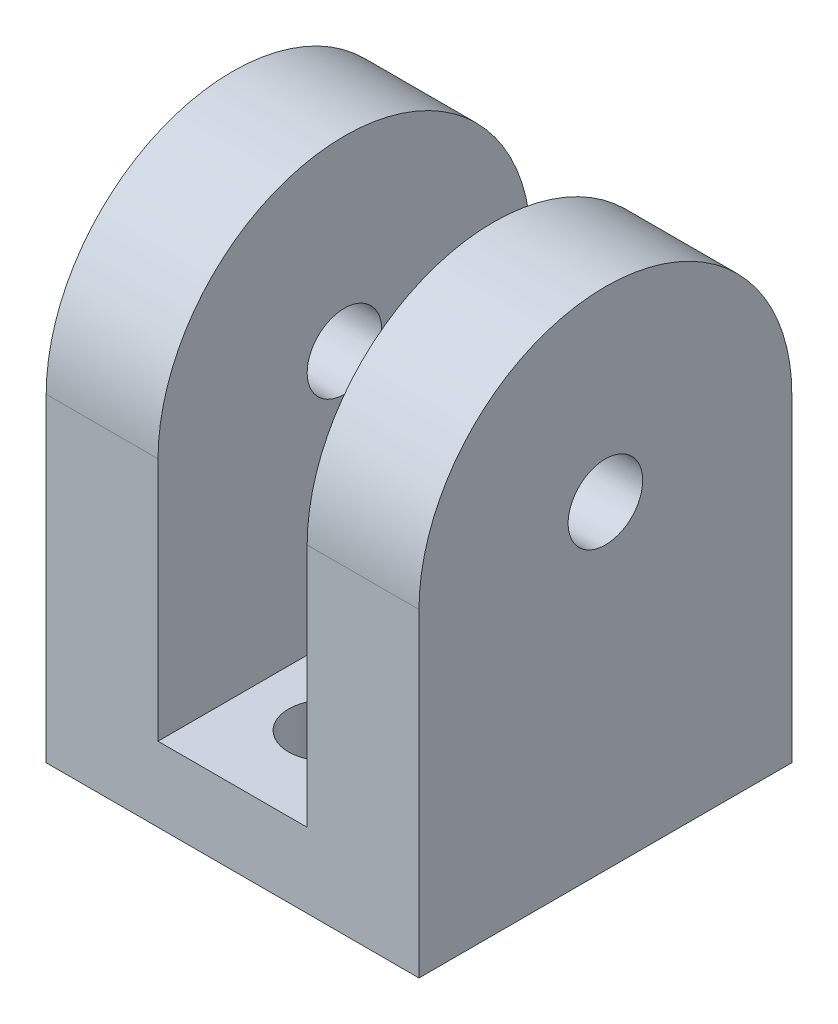
SolidWorks part; units mm, degrees
ref_plane "Front Plane" through (0, 0, 0) normal (0, 0, 1) x (1, 0, 0)
ref_plane "Top Plane" through (0, 0, 0) normal (0, 1, 0) x (1, 0, 0)
ref_plane "Right Plane" through (0, 0, 0) normal (1, 0, 0) x (0, 0, -1)
sketch "Sketch1" plane through (0, 0, 0) normal (0, 1, 0) x (1, 0, 0)
  line L1 (0, 0) -> (31.75, 0)
  line L2 (0, 0) -> (0, 31.75)
  line L3 (0, 31.75) -> (31.75, 31.75)
  line L4 (31.75, 0) -> (31.75, 31.75)
  dimension "D1" = 31.75
  dimension "D2" = 31.75
extrude "Boss-Extrude1" add sketch "Sketch1" along normal blind 50.8
sketch "Sketch2" plane through (31.75, 0, 0) normal (1, 0, 0) x (0, 0, -1)
  line L0 (0, 50.8) -> (31.75, 50.8)
  line L1 (31.75, 50.8) -> (31.75, 27.178)
  line L2 (31.75, 50.8) -> (31.75, 0) construction
  line L3 (0, 50.8) -> (0, 27.178)
  line L4 (0, 50.8) -> (0, 0) construction
  line L5 (0, 0) -> (31.75, 0) construction
  arc A0 (0, 27.178) -> (31.75, 27.178) centre (15.875, 27.178) cw
  dimension "D1" = 27.178
extrude "Cut-Extrude1" cut sketch "Sketch2" against normal through all
sketch "Sketch3" plane through (0, 0, 0) normal (0, 0, 1) x (1, 0, 0)
  line L0 (0, 0) -> (31.75, 0) construction
  line L1 (9.525, 6.35) -> (22.225, 6.35)
  line L2 (9.525, 6.35) -> (9.525, 57.15)
  line L3 (9.525, 57.15) -> (22.225, 57.15)
  line L4 (22.225, 6.35) -> (22.225, 57.15)
  line L7 (15.875, 27.178) -> (15.875, 0) construction
  line L8 (0, 27.178) -> (31.75, 27.178) construction
  dimension "D1" = 12.7
  dimension "D2" = 6.35
  dimension "D3" = 50.8
extrude "Cut-Extrude2" cut sketch "Sketch3" against normal through all
hole_wizard "1 (1) Diameter Hole1" positions "Sketch5" profile "Sketch6" hole size "1" standard "ANSI Inch" end condition through all
sketch "Sketch5" plane through (0, 6.35, 0) normal (0, 1, 0) x (1, 0, 0)
  line L0 (15.875, 31.75) -> (15.875, 0) construction
  line L1 (9.525, 31.75) -> (22.225, 31.75) construction
  line L2 (9.525, 0) -> (22.225, 0) construction
  line L3 (7.9752, 15.875) -> (23.7748, 15.875) construction
  point P8 (15.875, 23.8125)
  point P10 (15.875, 7.9375)
  point P17 (15.875, 15.875)
  dimension "D1" = 15.875
sketch "Sketch6" plane through (15.875, 6.35, -23.8125) normal (1, 0, 0) x (0, 0, 1)
  line L0 (0, 0) -> (0, 6.35)
  line L1 (0, 6.35) -> (3.175, 6.35)
  line L2 (3.175, 6.35) -> (3.175, 0)
  line L5 (3.175, 0) -> (0, 0)
  line L11 (0, -6.35) -> (0, 107.95) construction
  dimension "Thru Hole Dia." = 6.35
  dimension "Thru Hole Depth" = 6.35
hole_wizard "1 (1) Diameter Hole2" positions "Sketch8" profile "Sketch9" hole size "1" standard "ANSI Inch" end condition through all
sketch "Sketch8" plane through (31.75, 0, 0) normal (1, 0, 0) x (0, 0, -1)
  line L0 (0, 27.178) -> (31.75, 27.178) construction
  arc A0 (31.75, 27.178) -> (0, 27.178) centre (15.875, 27.178) ccw construction
  point P10 (15.875, 27.178)
sketch "Sketch9" plane through (31.75, 27.178, -15.875) normal (0, 1, 0) x (0, 0, -1)
  line L0 (0, 0) -> (0, 31.75)
  line L1 (0, 31.75) -> (3.175, 31.75)
  line L2 (3.175, 31.75) -> (3.175, 0)
  line L5 (3.175, 0) -> (0, 0)
  line L11 (0, -6.35) -> (0, 107.95) construction
  dimension "Thru Hole Dia." = 6.35
  dimension "Thru Hole Depth" = 31.75
